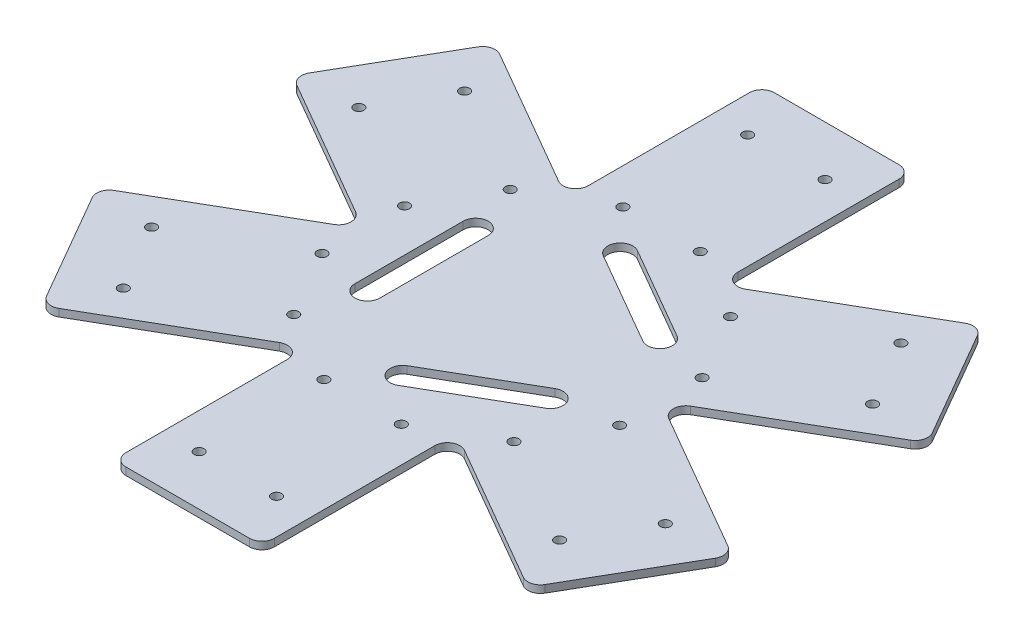
SolidWorks part; units mm, degrees
ref_plane "Plan de face" through (0, 0, 0) normal (0, 0, 1) x (1, 0, 0)
ref_plane "Plan de dessus" through (0, 0, 0) normal (0, 1, 0) x (1, 0, 0)
ref_plane "Plan de droite" through (0, 0, 0) normal (1, 0, 0) x (0, 0, -1)
sketch "Esquisse1" plane through (0, 0, 0) normal (0, 1, 0) x (1, 0, 0)
  line L0 (-150, 0) -> (-75, 129.9038) construction
  line L7 (-150, 0) -> (-75, -129.9038)
  line L8 (-75, -129.9038) -> (75, -129.9038)
  line L9 (75, -129.9038) -> (150, 0)
  line L10 (150, 0) -> (75, 129.9038)
  line L11 (75, 129.9038) -> (-75, 129.9038)
  line L12 (-75, 129.9038) -> (-150, 0)
  line L29 (-150, 0) -> (150, 0) construction
  line L30 (0, 129.9038) -> (0, -129.9038) construction
  line L31 (-75, -129.9038) -> (-75, 129.9038) construction
  line L32 (75, 129.9038) -> (75, -129.9038) construction
  line L33 (-150, 0) -> (78.9579, -132.1889) construction
  line L34 (150, 0) -> (-75, 129.9038) construction
  line L35 (-75, -129.9038) -> (150, 0) construction
  line L36 (-150, 0) -> (75, 129.9038) construction
  line L37 (-112.5, -64.9519) -> (112.5, 64.9519) construction
  line L38 (-112.5, 64.9519) -> (112.5, -64.9519) construction
  circle A0 centre (0, 0) radius 129.9038 construction
  circle A1 centre (15.5, -109.9038) radius 2
  circle A2 centre (-15.5, -109.9038) radius 2
  circle A3 centre (15.5, -59.9038) radius 2
  circle A4 centre (-15.5, -59.9038) radius 2
  circle A5 centre (-87.4295, -68.3753) radius 2
  circle A6 centre (-102.9295, -41.5285) radius 2
  circle A7 centre (-59.6282, -16.5285) radius 2
  circle A8 centre (-44.1282, -43.3753) radius 2
  circle A9 centre (-102.9295, 41.5285) radius 2
  circle A10 centre (-87.4295, 68.3753) radius 2
  circle A11 centre (-44.1282, 43.3753) radius 2
  circle A12 centre (-59.6282, 16.5285) radius 2
  circle A13 centre (-15.5, 109.9038) radius 2
  circle A14 centre (15.5, 109.9038) radius 2
  circle A15 centre (15.5, 59.9038) radius 2
  circle A16 centre (-15.5, 59.9038) radius 2
  circle A17 centre (87.4295, 68.3753) radius 2
  circle A18 centre (102.9295, 41.5285) radius 2
  circle A19 centre (59.6282, 16.5285) radius 2
  circle A20 centre (44.1282, 43.3753) radius 2
  circle A21 centre (102.9295, -41.5285) radius 2
  circle A22 centre (87.4295, -68.3753) radius 2
  circle A23 centre (44.1282, -43.3753) radius 2
  circle A24 centre (59.6282, -16.5285) radius 2
  point P1 (-112.5, 64.9519)
  point P11 (0, 129.9038)
  point P12 (-150, 0)
  point P69 (0, 0)
  dimension "D6" = 50
  dimension "D7" = 4
  dimension "D1" = 150
  dimension "D2" = 259.8076
  dimension "D3" = 129.9038
  dimension "D4" = 15.5
  dimension "D5" = 20
  dimension "D8" = 15.5
  dimension "D9" = 6
extrude "Boss.-Extru.1" add sketch "Esquisse1" along normal blind 3
fillet "Congé2" radius 10 1 edges at (-75, 1.5, -129.9038)
fillet "Congé3" radius 10 5 edges at (75, 1.5, -129.9038) (150, 1.5, 0) (75, 1.5, 129.9038) (-75, 1.5, 129.9038) (-150, 1.5, 0)
sketch "Esquisse3" plane through (0, 3, 0) normal (0, 1, 0) x (1, 0, 0)
  line L0 (-87.4295, -68.3753) -> (-44.1282, -43.3753) construction
  line L1 (-44.1282, -43.3753) -> (-15.5, -59.9038) construction
  line L2 (-15.5, -59.9038) -> (-15.5, -109.9038) construction
  line L3 (-29.8141, -129.9038) -> (-29.8141, -51.6396)
  line L4 (-69.2265, -129.9038) -> (69.2265, -129.9038) construction
  line L5 (-29.8141, -51.6396) -> (-97.5929, -90.7717)
  line L6 (-147.1132, -5) -> (-77.8868, -124.9038) construction
  line L7 (-29.8141, 51.6396) -> (-29.8141, 129.9038)
  line L8 (-97.5929, 90.7717) -> (-29.8141, 51.6396)
  line L9 (-59.7949, 0.2887) -> (-127.5737, 39.4208)
  line L10 (-127.5737, -38.8435) -> (-59.7949, 0.2887)
  line L11 (59.6282, 0) -> (127.4071, -39.1321)
  line L12 (127.4071, 39.1321) -> (59.6282, 0)
  line L13 (30.1474, 51.6396) -> (97.9263, 90.7717)
  line L14 (30.1474, 129.9038) -> (30.1474, 51.6396)
  line L15 (29.6474, -51.9282) -> (29.6474, -130.1925)
  line L16 (97.4263, -91.0604) -> (29.6474, -51.9282)
  line L17 (0, 129.9038) -> (0, -129.9038) construction
  line L18 (69.2265, 129.9038) -> (-69.2265, 129.9038) construction
  line L19 (-44.1282, 43.3753) -> (44.1282, 43.3753) construction
  line L20 (112.5, 64.9519) -> (-112.5, -64.9519) construction
  line L21 (147.1132, 5) -> (77.8868, 124.9038) construction
  line L22 (15.5, 59.9038) -> (59.6282, -16.5285) construction
  line L23 (0, 43.3753) -> (37.5641, 21.6876) construction
  line L24 (2.5, 47.7054) -> (40.0641, 26.0178)
  line L25 (-2.5, 39.0452) -> (35.0641, 17.3575)
  line L26 (36.4391, -21.0381) -> (-1.125, -42.7258) construction
  line L27 (38.9391, -25.3683) -> (1.375, -47.0559)
  line L28 (33.9391, -16.708) -> (-3.625, -38.3957)
  line L29 (-37.5641, -20.3886) -> (-37.5641, 22.9867) construction
  line L30 (-42.5641, -20.3886) -> (-42.5641, 22.9867)
  line L31 (-32.5641, -20.3886) -> (-32.5641, 22.9867)
  line L32 (-127.0737, -39.1321) -> (-59.2949, 0) [skipped]
  line L33 (-59.2949, 0) -> (-127.0737, 39.1321) [skipped]
  line L34 (-97.0929, 90.483) -> (-29.3141, 51.3509) [skipped]
  line L35 (-29.3141, 51.3509) -> (-29.3141, 129.6151) [skipped]
  line L36 (30.1474, 129.3265) -> (30.1474, 51.0622) [skipped]
  line L37 (30.1474, 51.0622) -> (97.9263, 90.1943) [skipped]
  line L38 (127.4071, 38.5548) -> (59.6282, -0.5774) [skipped]
  line L39 (59.6282, -0.5774) -> (127.4071, -39.7095) [skipped]
  arc A0 (2.5, 47.7054) -> (-2.5, 39.0452) centre (0, 43.3753) ccw
  arc A1 (35.0641, 17.3575) -> (40.0641, 26.0178) centre (37.5641, 21.6876) ccw
  arc A2 (38.9391, -25.3683) -> (33.9391, -16.708) centre (36.4391, -21.0381) ccw
  arc A3 (-3.625, -38.3957) -> (1.375, -47.0559) centre (-1.125, -42.7258) ccw
  arc A4 (-42.5641, -20.3886) -> (-32.5641, -20.3886) centre (-37.5641, -20.3886) ccw
  arc A5 (-32.5641, 22.9867) -> (-42.5641, 22.9867) centre (-37.5641, 22.9867) ccw
  point P33 (0.1667, -0.2887)
  point P50 (18.7821, 32.5315)
  point P56 (0, 0)
  point P60 (17.6571, -31.882)
  point P67 (-37.5641, 1.299)
  point P72 (-0.375, 0.6495)
  dimension "D1" = 6
  dimension "D2" = 10
  dimension "D3" = 3
  dimension "D4" = 3
extrude "Enlèv. mat.-Extru.1" cut sketch "Esquisse3" against normal through all
fillet "Congé4" radius 5 18 edges at (29.6474, 1.5, 129.9038) (29.6474, 1.5, 51.9282) (97.4263, 1.5, 91.0604) (-97.5929, 1.5, 90.7717) (-29.8141, 1.5, 51.6396) (-29.8141, 1.5, 129.9038) (127.4071, 1.5, 39.1321) (59.6282, 1.5, 0) (127.4071, 1.5, -39.1321) (30.1474, 1.5, -129.9038) (97.6763, 1.5, -90.6273) (30.1474, 1.5, -51.6396) (-29.8141, 1.5, -51.6396) (-29.8141, 1.5, -129.9038) (-97.5929, 1.5, -90.7717) (-127.3237, 1.5, -39.2765) (-59.7949, 1.5, -0.2887) (-127.5737, 1.5, 38.8435)
